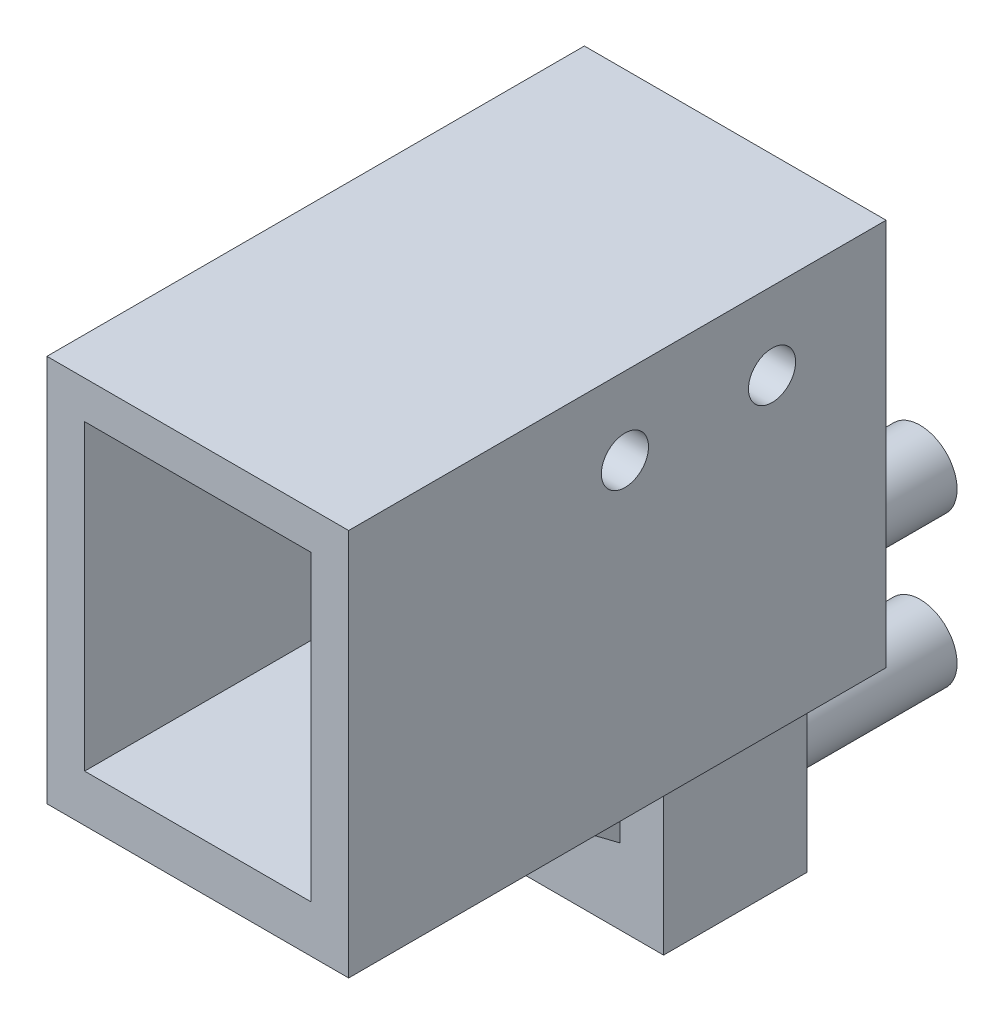
SolidWorks part; units mm, degrees
ref_plane "Front Plane" through (0, 0, 0) normal (0, 0, 1) x (1, 0, 0)
ref_plane "Top Plane" through (0, 0, 0) normal (0, 1, 0) x (1, 0, 0)
ref_plane "Right Plane" through (0, 0, 0) normal (1, 0, 0) x (0, 0, -1)
sketch "Sketch1" plane through (0, 0, 0) normal (0, 1, 0) x (1, 0, 0)
  line L1 (-7.6, -7.6) -> (7.6, -7.6)
  line L2 (-7.6, -7.6) -> (-7.6, 7.6)
  line L3 (-7.6, 7.6) -> (7.6, 7.6)
  line L4 (7.6, -7.6) -> (7.6, 7.6)
  line L5 (-7.6, -7.6) -> (7.6, 7.6) construction
  line L6 (-7.6, 7.6) -> (7.6, -7.6) construction
  point P4 (0, 0)
  dimension "D1" = 15.2
  dimension "D2" = 15.2
extrude "Boss-Extrude1" add sketch "Sketch1" along normal mid plane 28
sketch "Sketch2" plane through (0, 0, -7.6) normal (0, 0, 1) x (1, 0, 0)
  line L0 (0, -8.36) -> (0, 8.36) construction
  line L1 (0, 9.55) -> (0, -6.45) construction
  line L2 (0, 13.475) -> (0, 14) construction
  line L3 (-7.6, 14) -> (7.6, 14) construction
  line L4 (0, -10.375) -> (0, -14) construction
  line L5 (-7.6, -14) -> (7.6, -14) construction
  circle A0 centre (0, -6.45) radius 3.925
  circle A1 centre (0, 9.55) radius 3.925
  dimension "D1" = 7.85
  dimension "D2" = 7.85
  dimension "D3" = 16
  dimension "D4" = 0.525
extrude "Boss-Extrude3" add sketch "Sketch2" against normal blind 19.6
sketch "Sketch3" plane through (0, 14, 0) normal (0, 1, 0) x (1, 0, 0)
  line L0 (7.6, 7.6) -> (-7.6, 7.6) construction
  line L1 (-16, -49.4) -> (16, -49.4)
  line L2 (-16, -49.4) -> (-16, 7.6)
  line L3 (-16, 7.6) -> (16, 7.6)
  line L4 (16, -49.4) -> (16, 7.6)
  line L5 (-16, -49.4) -> (16, 7.6) construction
  line L6 (-16, 7.6) -> (16, -49.4) construction
  line L8 (0, -8.36) -> (0, 8.36) construction
  point P4 (0, -20.9)
  point P9 (0, 0)
  point P11 (12.6561, 0)
  point P12 (0, 0)
  dimension "D1" = 32
  dimension "D2" = 57
extrude "Boss-Extrude5" add sketch "Sketch3" against normal blind 5
sketch "Sketch9" plane through (0, 0, -7.6) normal (0, 0, -1) x (-1, 0, 0)
  line L0 (-16, 14) -> (16, 14)
  line L3 (-16, 46.1) -> (-16, 14)
  line L4 (-12, 46.1) -> (-12, 14)
  line L6 (12, 14) -> (12, 46.1)
  line L8 (-16, 46.1) -> (-16, 50.1)
  line L18 (-12, 46.1) -> (12, 46.1)
  line L22 (-16, 50.1) -> (16, 50.1)
  line L24 (16, 50.1) -> (16, 14)
  point P5 (-12, 45.4185)
  point P6 (-12, 45.8)
  point P8 (12, 45.4185)
  dimension "D1" = 24
  dimension "D2" = 4
  dimension "D3" = 32.1
  dimension "D5" = 4
extrude "Boss-Extrude7" add sketch "Sketch9" against normal up to surface (57 mm away) up to face at (0, 11.5, 49.4)
sketch "Sketch5" plane through (0, 0, 0) normal (1, 0, 0) x (0, 0, -1)
  line L6 (-7.6, -6) -> (-7.6, 9)
  line L7 (-7.6, 9) -> (-7.6, -14) construction
  line L8 (-7.6, 9) -> (-27.6, 9)
  line L9 (-49.4, 9) -> (7.6, 9) construction
  line L10 (-27.6, 9) -> (-7.6, -6)
  dimension "D1" = 15
  dimension "D2" = 20
extrude "Boss-Extrude6" add sketch "Sketch5" along normal mid plane 6
sketch "Sketch11" plane through (0, 0, 0) normal (1, 0, 0) x (0, 0, -1)
  line L0 (7.6, 50.1) -> (7.6, 46.1) construction
  line L1 (7.6, 9) -> (7.6, 50.1) construction
  line L2 (7.6, 46.1) -> (-4.5, 46.1) construction
  line L3 (-4.5, 46.1) -> (-4.5, 41.9) construction
  line L4 (-4.5, 41.9) -> (-20.1, 41.9) construction
  circle A0 centre (-20.1, 41.9) radius 2.5
  circle A1 centre (-4.5, 41.9) radius 2.5
  dimension "D5" = 5
  dimension "D6" = 5
  dimension "D1" = 4
  dimension "D2" = 4.2
  dimension "D3" = 12.1
  dimension "D4" = 15.6
extrude "Cut-Extrude1" cut sketch "Sketch11" against normal through all both and the other way through all
equation "\"Tetrix Block Width\"= 15.2"
equation "\"D1@Boss-Extrude3\"=\"Tetrix Block Width\" + 0.4 + 4"
equation "\"D1@Sketch3\"=24+4+4"
